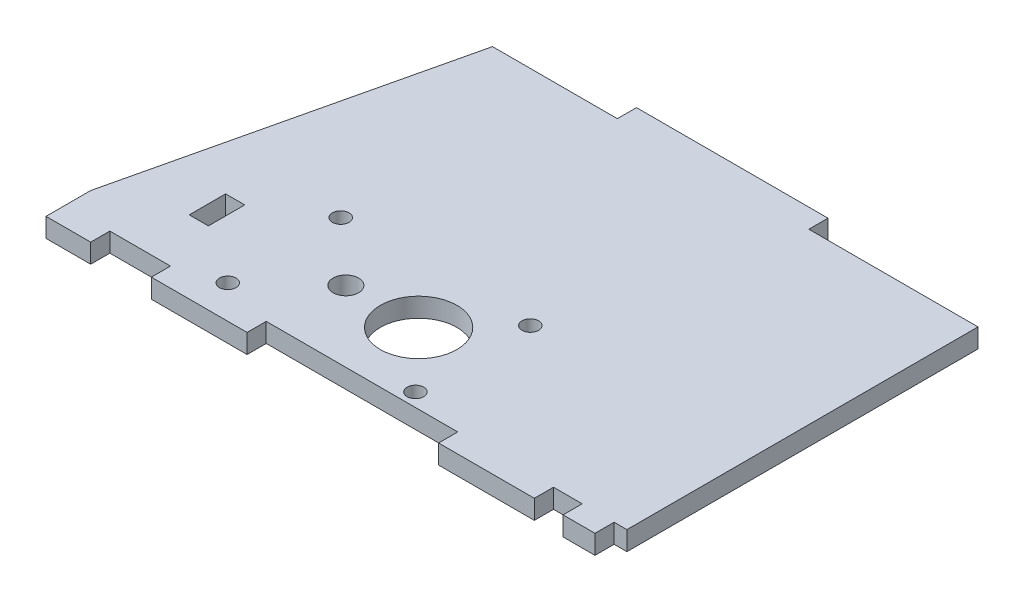
SolidWorks part; units mm, degrees
ref_plane "Front Plane" through (0, 0, 0) normal (0, 0, 1) x (1, 0, 0)
ref_plane "Top Plane" through (0, 0, 0) normal (0, 1, 0) x (1, 0, 0)
ref_plane "Right Plane" through (0, 0, 0) normal (1, 0, 0) x (0, 0, -1)
sketch "Sketch1" plane through (0, 0, 0) normal (0, 1, 0) x (1, 0, 0)
  line L0 (-95.7406, 27.8534) -> (-80.7406, 27.8534)
  line L1 (-80.7406, 27.8534) -> (-80.7406, 30.8534)
  line L2 (-80.7406, 30.8534) -> (-50.7406, 30.8534)
  line L3 (-95.7406, -30.1466) -> (-80.7406, -30.1466)
  line L4 (-80.7406, -30.1466) -> (-80.7406, -27.1466)
  line L5 (-80.7406, -27.1466) -> (-50.7406, -27.1466)
  line L6 (-50.7406, -30.1466) -> (-50.7406, -27.1466)
  line L7 (-35.7406, -30.1466) -> (-50.7406, -30.1466)
  line L8 (-50.7406, 27.8534) -> (-50.7406, 30.8534)
  line L9 (-35.7406, 27.8534) -> (-50.7406, 27.8534)
  line L10 (-35.7406, -30.1466) -> (-35.7406, -27.1466)
  line L11 (-35.7406, -27.1466) -> (-31.2406, -27.1466)
  line L12 (-31.2406, -27.1466) -> (-31.2406, -30.1466)
  line L13 (-31.2406, -30.1466) -> (-26.2406, -30.1466)
  line L14 (-105.2406, -30.1466) -> (-105.2406, -27.1466)
  line L15 (-112.2406, -27.1466) -> (-112.2406, -30.1466)
  line L16 (-112.2406, -30.1466) -> (-105.2406, -30.1466)
  line L17 (-105.2406, -27.1466) -> (-95.7406, -27.1466)
  line L18 (-95.7406, -27.1466) -> (-95.7406, -30.1466)
  line L19 (-112.2406, -27.1466) -> (-112.2406, -23.1466)
  line L20 (-35.7406, 27.8534) -> (-26.2406, 27.8534)
  line L27 (-95.7406, 27.8534) -> (-100.2906, 27.8534)
  line L28 (-100.2906, 27.8534) -> (-112.2406, -23.1466)
  line L30 (-26.2406, -27.1466) -> (-24.2406, -27.1466)
  line L31 (-24.2406, -27.1466) -> (-24.2406, 27.8534)
  line L32 (-24.2406, 27.8534) -> (-26.2406, 27.8534)
  line L33 (-26.2406, -30.1466) -> (-26.2406, -27.1466)
  line L40 (-98.2202, -18.7291) -> (-101.2202, -18.7291)
  line L41 (-101.2202, -18.7291) -> (-101.2202, -13.0323)
  line L44 (-98.2202, -13.0323) -> (-98.2202, -18.7291)
  line L45 (-101.2202, -13.0323) -> (-98.2202, -13.0323)
  circle A0 centre (-79.3834, -16.0323) radius 2
  circle A1 centre (-67.9834, -16.0323) radius 6
  circle A2 centre (-59.4834, -25.0323) radius 1.3
  circle A3 centre (-59.4834, -7.0323) radius 1.3
  circle A4 centre (-88.9834, -7.2323) radius 1.3
  circle A5 centre (-88.9834, -24.9323) radius 1.3
extrude "Boss-Extrude1" add sketch "Sketch1" along normal blind 3
